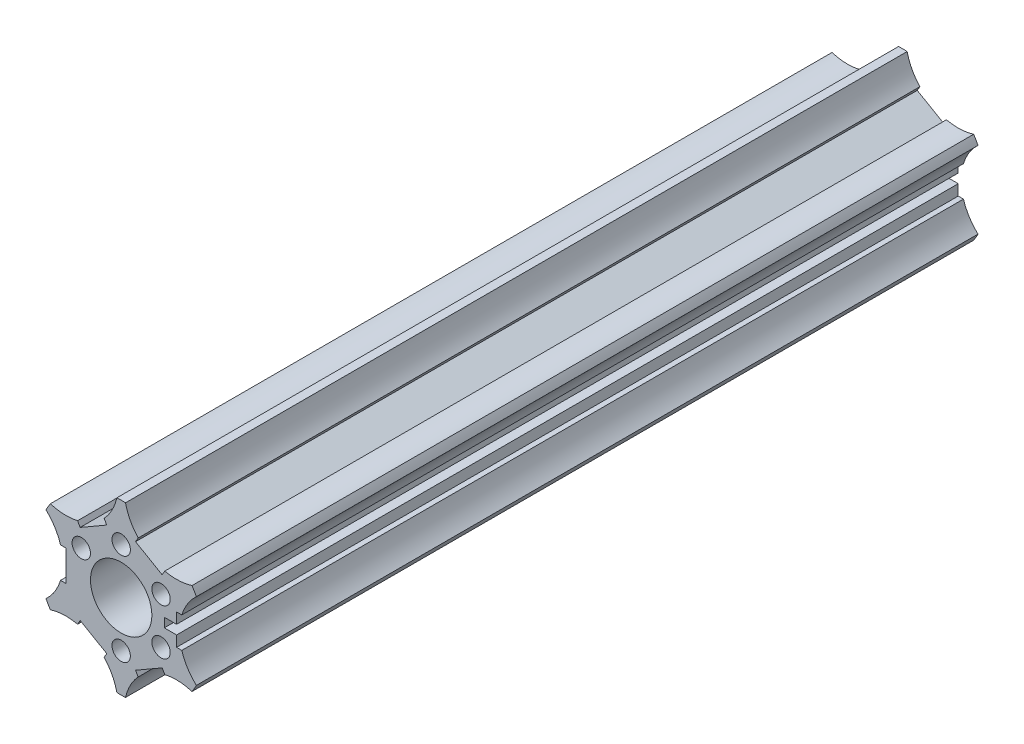
SolidWorks part; units mm, degrees
ref_plane "Plan de face" through (0, 0, 0) normal (0, 0, 1) x (1, 0, 0)
ref_plane "Plan de dessus" through (0, 0, 0) normal (0, 1, 0) x (1, 0, 0)
ref_plane "Plan de droite" through (0, 0, 0) normal (1, 0, 0) x (0, 0, -1)
sketch "Esquisse1" plane through (0, 0, 0) normal (0, 0, 1) x (1, 0, 0)
  line L0 (-36, 0) -> (36, 0) construction
  line L2 (0, 0) -> (0, -53.5) construction
  line L8 (-50.7224, 8.5) -> (-36, 0) construction
  line L9 (-36, 0) -> (-50.7224, -8.5) construction
  line L12 (-18, -51.1769) -> (-18, -48.1769)
  line L17 (-34.6353, -19.9967) -> (0, 0) construction
  line L19 (-50.7224, 8.5) -> (-53.3205, 10)
  line L20 (-32.7224, 39.6769) -> (-35.3205, 41.1769)
  line L21 (-18, 51.1769) -> (-18, 48.1769)
  line L23 (-50.7224, -8.5) -> (-53.3205, -10)
  line L25 (-32.7224, -39.6769) -> (-35.3205, -41.1769)
  line L26 (50.7224, -8.5) -> (53.3205, -10)
  line L27 (32.7224, -39.6769) -> (35.3205, -41.1769)
  line L28 (18, -51.1769) -> (18, -48.1769)
  line L30 (18, 51.1769) -> (18, 48.1769)
  line L31 (32.7224, 39.6769) -> (35.3205, 41.1769)
  line L32 (50.7224, 8.5) -> (53.3205, 10)
  circle A0 centre (0, 0) radius 18 construction
  circle A1 centre (36, 0) radius 18 construction
  circle A2 centre (-36, 0) radius 18 construction
  circle A3 centre (-18, -31.1769) radius 18 construction
  circle A4 centre (18, -31.1769) radius 18 construction
  circle A6 centre (0, 0) radius 53.5 construction
  circle A7 centre (0, 0) radius 17 construction
  circle A8 centre (36, 0) radius 17 construction
  circle A11 centre (18, -31.1769) radius 17 construction
  arc A12 (-50.7224, 8.5) -> (-50.7224, -8.5) centre (-36, 0) cw
  circle A24 centre (-36, 0) radius 20 construction
  arc A25 (-53.3205, -10) -> (-34.5498, -19.9474) centre (-36, 0) ccw
  arc A26 (-18, -48.1769) -> (-32.7224, -39.6769) centre (-18, -31.1769) ccw
  arc A27 (-35.3205, -41.1769) -> (-34.5498, -19.9474) centre (-18, -31.1769) cw
  arc A29 (-18, -51.1769) -> (0, -39.8947) centre (-18, -31.1769) ccw
  arc A32 (53.3205, -10) -> (34.5498, -19.9474) centre (36, 0) cw
  arc A33 (35.3205, -41.1769) -> (34.5498, -19.9474) centre (18, -31.1769) ccw
  arc A34 (18, -48.1769) -> (32.7224, -39.6769) centre (18, -31.1769) cw
  arc A35 (18, -51.1769) -> (0, -39.8947) centre (18, -31.1769) cw
  arc A36 (-53.3205, 10) -> (-34.5498, 19.9474) centre (-36, 0) cw
  arc A37 (-35.3205, 41.1769) -> (-34.5498, 19.9474) centre (-18, 31.1769) ccw
  arc A38 (-18, 48.1769) -> (-32.7224, 39.6769) centre (-18, 31.1769) cw
  arc A39 (-18, 51.1769) -> (0, 39.8947) centre (-18, 31.1769) cw
  arc A40 (18, 51.1769) -> (0, 39.8947) centre (18, 31.1769) ccw
  arc A41 (18, 48.1769) -> (32.7224, 39.6769) centre (18, 31.1769) ccw
  arc A42 (35.3205, 41.1769) -> (34.5498, 19.9474) centre (18, 31.1769) cw
  arc A43 (53.3205, 10) -> (34.5498, 19.9474) centre (36, 0) ccw
  arc A44 (50.7224, -8.5) -> (50.7224, 8.5) centre (36, 0) cw
  point P11 (0, 0)
  point P15 (0, 0)
  point P16 (0, 0)
  point P48 (0, 0)
  point P61 (0, 0)
  point P69 (0, 0)
  dimension "D1" = 36
  dimension "D2" = 3
  dimension "D5" = 17
  dimension "D6" = 17
  dimension "D7" = 60
  dimension "D10" = 3
  dimension "D11" = 2
  dimension "D13" = 107
  dimension "D3" = 36
extrude "Boss.-Extru.1" add sketch "Esquisse1" along normal blind 254.6667
sketch "Esquisse4" plane through (0, 0, 254.6667) normal (0, 0, 1) x (1, 0, 0)
  circle A3 centre (0, 0) radius 27.5
  circle A5 centre (0, 0) radius 54.2501
  dimension "D1" = 55
extrude "Enlèv. mat.-Extru.1" cut sketch "Esquisse4" against normal through all
sketch "Esquisse5" plane through (0, 0, 254.6667) normal (0, 0, 1) x (1, 0, 0)
  line L0 (14.2061, -14.6057) -> (5.5458, -19.6057)
  line L1 (18.0519, 5) -> (19.7519, 5)
  line L2 (18.0519, 5) -> (18.0519, -5) construction
  line L3 (18.0519, -5) -> (19.7519, -5)
  line L4 (19.7519, 5) -> (19.7519, -5)
  line L5 (4.6958, -18.1334) -> (5.5458, -19.6057)
  line L6 (13.3561, -13.1334) -> (4.6958, -18.1334)
  line L7 (13.3561, -13.1334) -> (14.2061, -14.6057)
  line L8 (-5.5458, -19.6057) -> (-14.2061, -14.6057)
  line L9 (-13.3561, -13.1334) -> (-14.2061, -14.6057)
  line L10 (-4.6958, -18.1334) -> (-13.3561, -13.1334)
  line L11 (-4.6958, -18.1334) -> (-5.5458, -19.6057)
  line L12 (-19.7519, -5) -> (-19.7519, 5)
  line L13 (-18.0519, 5) -> (-19.7519, 5)
  line L14 (-18.0519, -5) -> (-18.0519, 5)
  line L15 (-18.0519, -5) -> (-19.7519, -5)
  line L16 (-14.2061, 14.6057) -> (-5.5458, 19.6057)
  line L17 (-4.6958, 18.1334) -> (-5.5458, 19.6057)
  line L18 (-13.3561, 13.1334) -> (-4.6958, 18.1334)
  line L19 (-13.3561, 13.1334) -> (-14.2061, 14.6057)
  line L20 (5.5458, 19.6057) -> (14.2061, 14.6057)
  line L21 (13.3561, 13.1334) -> (14.2061, 14.6057)
  line L22 (4.6958, 18.1334) -> (13.3561, 13.1334)
  line L23 (4.6958, 18.1334) -> (5.5458, 19.6057)
  line L24 (0, 15) -> (0, 0) construction
  line L25 (18.0519, 5) -> (18.0519, 1.5)
  line L26 (18.0519, 1.5) -> (14.0519, 1.5)
  line L27 (14.0519, 1.5) -> (14.0519, -1.5)
  line L28 (14.0519, -1.5) -> (18.0519, -1.5)
  line L29 (18.0519, -1.5) -> (18.0519, -5)
  line L30 (0, 0) -> (18.0519, 0) construction
  line L31 (-12.9904, 7.5) -> (12.9904, -7.5) construction
  arc A0 (24.4896, 12.5104) -> (24.4896, -12.5104) centre (36, 0) ccw construction
  circle A1 centre (0, 0) radius 10
  circle A2 centre (0, 15) radius 3
  circle A3 centre (12.9904, 7.5) radius 3
  circle A4 centre (12.9904, -7.5) radius 3
  circle A5 centre (0, -15) radius 3
  circle A6 centre (-12.9904, 7.5) radius 3
  point P29 (0, 0)
  point P42 (0, 0)
  point P49 (0, 0)
  dimension "D3" = 20
  dimension "D4" = 6
  dimension "D6" = 4
  dimension "D1" = 1.7
  dimension "D2" = 10
  dimension "D5" = 15
  dimension "D7" = 6
  dimension "D8" = 3
  dimension "D9" = 3
  dimension "D10" = 4
extrude "Enlèv. mat.-Extru.2" cut sketch "Esquisse5" against normal through all
sketch "Esquisse6"
sketch_block_instance "Bloc1-1"
sketch_block "Bloc1" parameters "D1"=2
